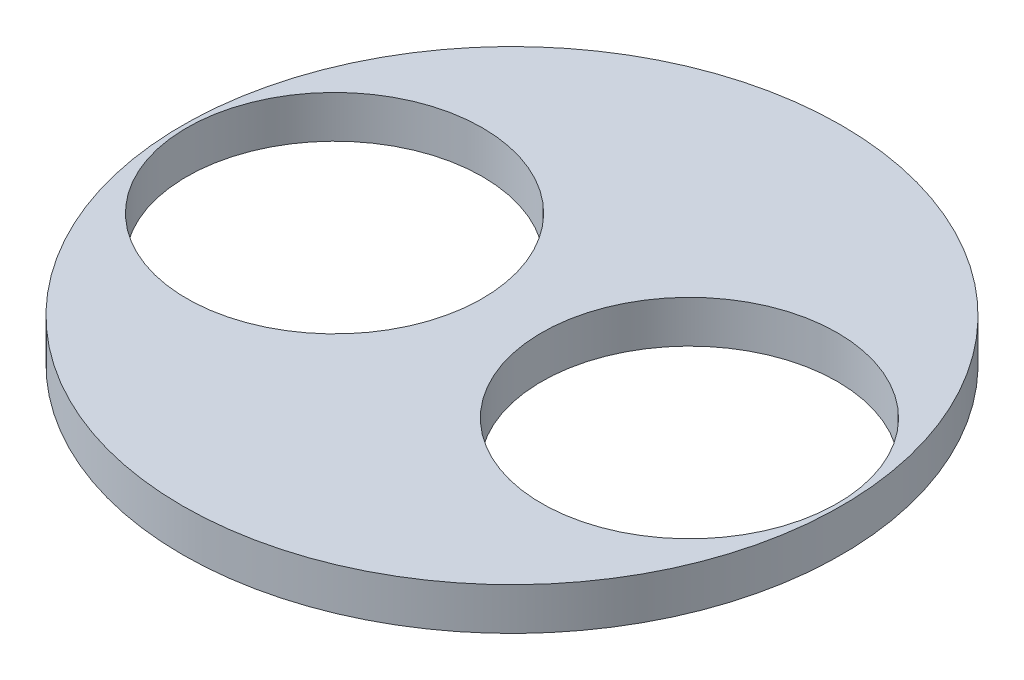
SolidWorks part; units mm, degrees
material "Acrylic (Medium-high impact)"
ref_plane "Front Plane" through (0, 0, 0) normal (0, 0, 1) x (1, 0, 0)
ref_plane "Top Plane" through (0, 0, 0) normal (0, 1, 0) x (1, 0, 0)
ref_plane "Right Plane" through (0, 0, 0) normal (1, 0, 0) x (0, 0, -1)
sketch "Sketch1" plane through (0, 0, 0) normal (0, 1, 0) x (1, 0, 0)
  circle A0 centre (0, 0) radius 49.53
  dimension "D1" = 99.06
extrude "Boss-Extrude1" add sketch "Sketch1" along normal blind 6.35
sketch "Sketch2" plane through (0, 0, 0) normal (0, -1, 0) x (-1, 0, 0)
  line L0 (49.53, 0) -> (-49.53, 0) construction
  circle A0 centre (26.67, 0) radius 22.225
  circle A1 centre (-26.67, 0) radius 22.225
  circle A2 centre (0, 0) radius 49.53 construction
  point P8 (26.67, 0)
  dimension "D1" = 44.45
extrude "Cut-Extrude1" cut sketch "Sketch2" against normal through all
